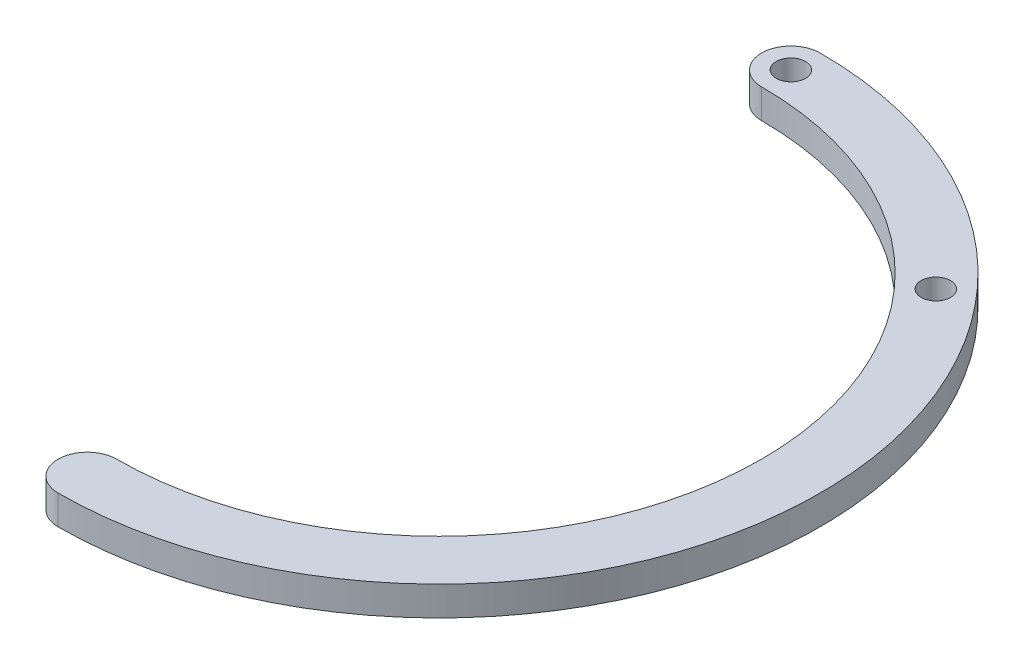
SolidWorks part; units mm, degrees
ref_plane "Front Plane" through (0, 0, 0) normal (0, 0, 1) x (1, 0, 0)
ref_plane "Top Plane" through (0, 0, 0) normal (0, 1, 0) x (1, 0, 0)
ref_plane "Right Plane" through (0, 0, 0) normal (1, 0, 0) x (0, 0, -1)
sketch "Sketch2" plane through (0, 0, 0) normal (0, 1, 0) x (1, 0, 0)
  circle A0 centre (0, 0) radius 38.1 construction
  circle A1 centre (28.3981, 25.4) radius 1.5875
  arc A2 (0, 38.1) -> (0, -38.1) centre (0, 0) cw construction
  arc A3 (0, -41.275) -> (0, 41.275) centre (0, 0) ccw
  arc A4 (0, -34.925) -> (0, 34.925) centre (0, 0) ccw
  arc A5 (0, -34.925) -> (0, -41.275) centre (0, -38.1) ccw
  arc A6 (0, 41.275) -> (0, 34.925) centre (0, 38.1) ccw
  circle A7 centre (0, 38.1) radius 1.5875
  point P6 (38.1, 0)
  dimension "D1" = 76.2
  dimension "D2" = 3.175
  dimension "D4" = 3.175
  dimension "D5" = 12.7
  dimension "D3" = 90
extrude "Boss-Extrude1" add sketch "Sketch2" along normal blind 3.175
